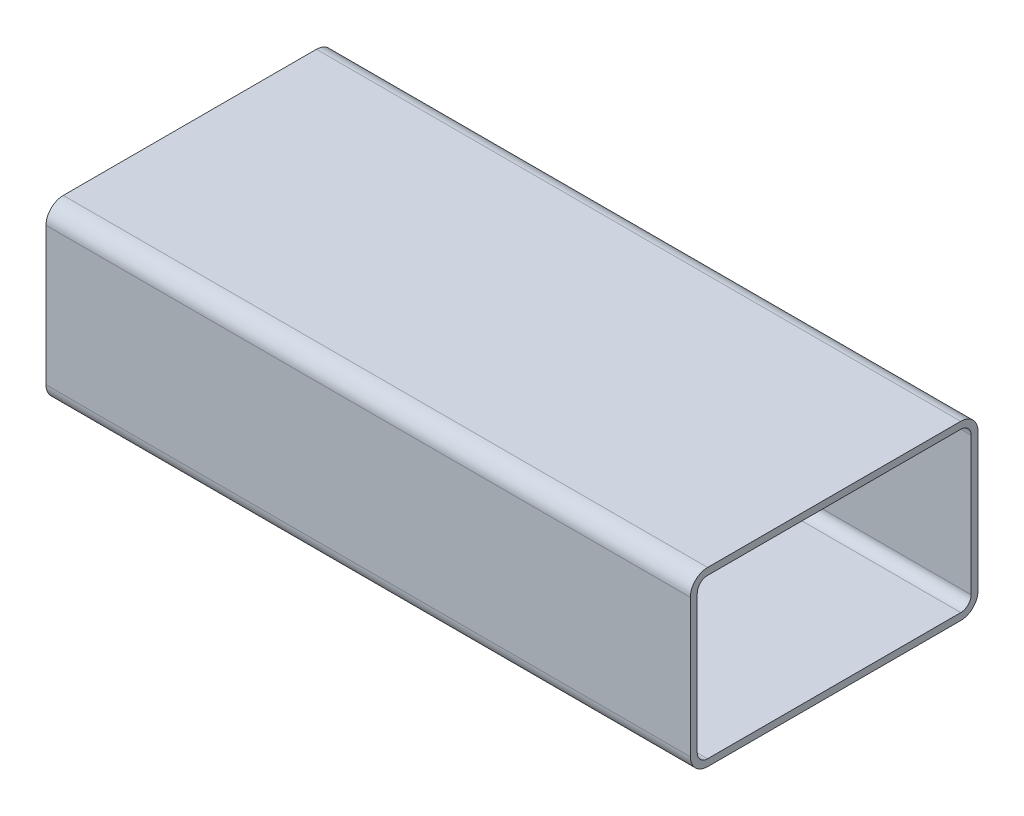
SolidWorks part; units mm, degrees
material "AISI 304"
ref_plane "Plano frontal" through (0, 0, 0) normal (0, 0, 1) x (1, 0, 0)
ref_plane "Plano superior" through (0, 0, 0) normal (0, 1, 0) x (1, 0, 0)
ref_plane "Plano direito" through (0, 0, 0) normal (1, 0, 0) x (0, 0, -1)
sketch "Esboço1" plane through (0, 0, 0) normal (0, 0, 1) x (1, 0, 0)
  line L0 (0, 0) -> (112, 0)
  dimension "D1" = 112
other "Tubo retangular 50 X 30 X 2.6(1)"
ref_plane "Plano1" through (0, 0, 0) normal (1, 0, 0) x (0, 1, 0)
sketch "Sketch1" plane through (0, 0, 0) normal (1, 0, 0) x (0, 1, 0)
  line L0 (-12, -23.8) -> (12, -23.8)
  line L1 (-13.8, -22) -> (-13.8, 22)
  line L2 (12, 23.8) -> (-12, 23.8)
  line L3 (13.8, 22) -> (13.8, -22)
  line L4 (-12, -25) -> (12, -25)
  line L5 (-15, -22) -> (-15, 22)
  line L6 (12, 25) -> (-12, 25)
  line L7 (15, 22) -> (15, -22)
  arc A0 (15, 22) -> (12, 25) centre (12, 22) ccw
  arc A1 (12, -25) -> (15, -22) centre (12, -22) ccw
  arc A2 (-15, -22) -> (-12, -25) centre (-12, -22) ccw
  arc A3 (-12, 25) -> (-15, 22) centre (-12, 22) ccw
  arc A4 (-12, 23.8) -> (-13.8, 22) centre (-12, 22) ccw
  arc A5 (13.8, 22) -> (12, 23.8) centre (12, 22) ccw
  arc A6 (12, -23.8) -> (13.8, -22) centre (12, -22) ccw
  arc A7 (-13.8, -22) -> (-12, -23.8) centre (-12, -22) ccw
  point P0 (0, 25)
  point P1 (15, 0)
  point P2 (0, -25)
  point P3 (-15, 0)
  point P4 (-15, 25)
  point P5 (15, 25)
  point P6 (15, -25)
  point P7 (-15, -25)
  point P8 (0, 0)
  point P33 (0, 0)
  dimension "D1" = 3
  dimension "Thickness" = 1.2
  dimension "V_leg" = 50
  dimension "H_leg" = 30
